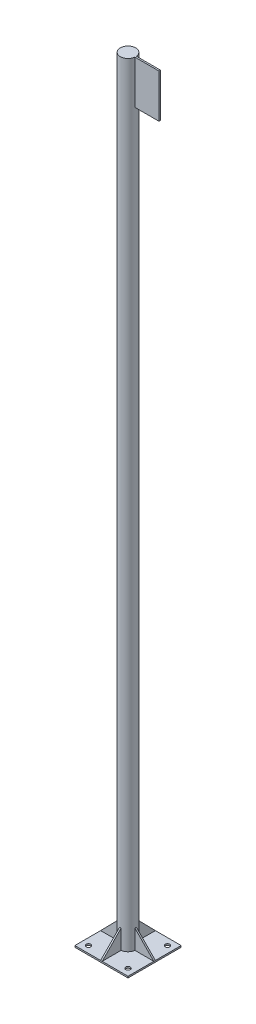
SolidWorks part; units mm, degrees
ref_plane "Alzado" through (0, 0, 0) normal (0, 0, 1) x (1, 0, 0)
ref_plane "Planta" through (0, 0, 0) normal (0, 1, 0) x (1, 0, 0)
ref_plane "Vista lateral" through (0, 0, 0) normal (1, 0, 0) x (0, 0, -1)
sketch "Croquis1" plane through (0, 0, 0) normal (0, 1, 0) x (1, 0, 0)
  line L1 (0, 0) -> (220, 0)
  line L2 (0, 0) -> (0, 220)
  line L3 (0, 220) -> (220, 220)
  line L4 (220, 0) -> (220, 220)
  dimension "D1" = 220
  dimension "D2" = 220
extrude "Saliente-Extruir1" add sketch "Croquis1" along normal blind 6.35
sketch "Croquis2" plane through (0, 6.35, 0) normal (0, 1, 0) x (1, 0, 0)
  line L0 (110, 220) -> (110, 0) construction
  line L1 (220, 220) -> (0, 220) construction
  line L2 (0, 0) -> (220, 0) construction
  circle A0 centre (110, 110) radius 31.75
  dimension "D1" = 63.5
extrude "Saliente-Extruir2" add sketch "Croquis2" along normal blind 3200
sketch "Croquis3" plane through (0, 6.35, 0) normal (0, 1, 0) x (1, 0, 0)
  line L0 (0, 110) -> (220, 110) construction
  line L1 (0, 220) -> (0, 0) construction
  line L2 (220, 0) -> (220, 220) construction
  line L3 (0, 113.175) -> (78.4091, 113.175)
  line L4 (0, 106.825) -> (78.4091, 106.825)
  line L5 (0, 106.825) -> (0, 113.175)
  line L6 (110, 220) -> (110, 0) construction
  line L7 (220, 220) -> (0, 220) construction
  line L8 (0, 0) -> (220, 0) construction
  line L9 (106.825, 220) -> (106.825, 141.5909)
  line L10 (113.175, 220) -> (113.175, 141.5909)
  line L11 (106.825, 220) -> (113.175, 220)
  line L12 (106.825, 0) -> (113.175, 0)
  line L13 (113.175, 0) -> (113.175, 78.4091)
  line L14 (106.825, 0) -> (106.825, 78.4091)
  line L15 (220, 106.825) -> (220, 113.175)
  line L16 (220, 106.825) -> (141.5909, 106.825)
  line L17 (220, 113.175) -> (141.5909, 113.175)
  circle A0 centre (110, 110) radius 31.75 construction
  arc A1 (78.4091, 106.825) -> (78.4091, 113.175) centre (110, 110) cw
  circle A2 centre (110, 110) radius 31.75 construction
  arc A3 (106.825, 141.5909) -> (113.175, 141.5909) centre (110, 110) cw
  arc A4 (106.825, 78.4091) -> (113.175, 78.4091) centre (110, 110) ccw
  arc A5 (141.5909, 106.825) -> (141.5909, 113.175) centre (110, 110) ccw
  dimension "D1" = 3.175
  dimension "D2" = 3.175
extrude "Saliente-Extruir3" add sketch "Croquis3" along normal blind 80
sketch "Croquis4" plane through (0, 0, -106.825) normal (0, 0, 1) x (1, 0, 0)
  line L0 (78.4091, 86.35) -> (0, 6.35)
  line L1 (0, 6.35) -> (0, 86.35)
  line L2 (0, 86.35) -> (78.4091, 86.35)
  line L3 (141.5909, 86.35) -> (220, 86.35)
  line L4 (220, 86.35) -> (220, 6.35)
  line L5 (220, 6.35) -> (141.5909, 86.35)
extrude "Cortar-Extruir1" cut sketch "Croquis4" against normal blind 6.35
sketch "Croquis5" plane through (106.825, 0, 0) normal (-1, 0, 0) x (0, 0, 1)
  line L0 (-220, 6.35) -> (-141.5909, 86.35)
  line L1 (-141.5909, 86.35) -> (-220, 86.35)
  line L2 (-220, 86.35) -> (-220, 6.35)
  line L3 (-78.4091, 86.35) -> (0, 6.35)
  line L4 (0, 6.35) -> (0, 86.35)
  line L5 (0, 86.35) -> (-78.4091, 86.35)
extrude "Cortar-Extruir2" cut sketch "Croquis5" against normal blind 6.35
sketch "Croquis6" plane through (0, 6.35, 0) normal (0, 1, 0) x (1, 0, 0)
  line L0 (220, 220) -> (110, 110) construction
  line L1 (220, 110) -> (110, 110) construction
  line L2 (220, 113.175) -> (220, 106.825) construction
  line L3 (110, 220) -> (110, 0) construction
  line L4 (113.175, 220) -> (106.825, 220) construction
  line L5 (113.175, 0) -> (106.825, 0) construction
  circle A0 centre (191.7157, 191.7157) radius 9.525
  circle A1 centre (191.7157, 28.2843) radius 9.525
  circle A2 centre (28.2843, 28.2843) radius 9.525
  circle A3 centre (28.2843, 191.7157) radius 9.525
  dimension "D1" = 19.05
  dimension "D2" = 40
extrude "Cortar-Extruir3" cut sketch "Croquis6" against normal blind 6.35
sketch "Croquis7" plane through (0, 3206.35, 0) normal (0, 1, 0) x (1, 0, 0)
  line L0 (241.5909, 113.175) -> (141.5909, 113.175)
  line L1 (241.5909, 106.825) -> (141.5909, 106.825)
  line L2 (241.5909, 113.175) -> (241.5909, 106.825)
  arc A0 (141.5909, 113.175) -> (141.5909, 106.825) centre (110, 110) cw
  dimension "D1" = 100
extrude "Saliente-Extruir4" add sketch "Croquis7" against normal blind 180
